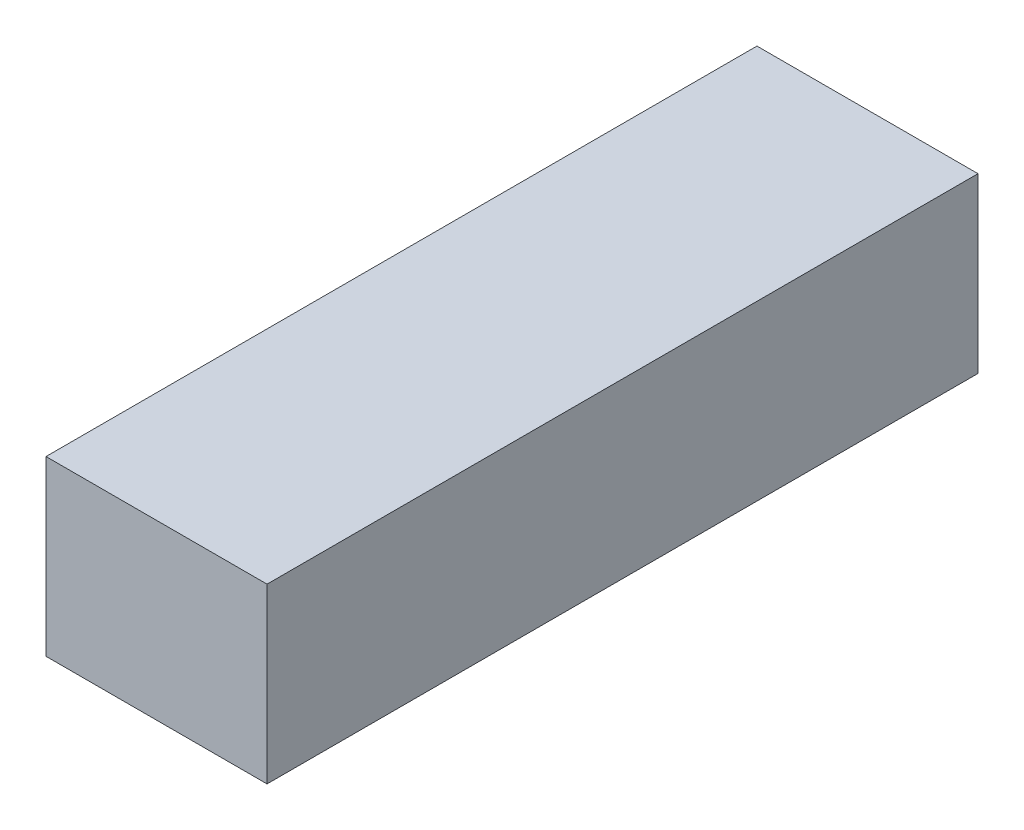
SolidWorks part; units mm, degrees
ref_plane "Front Plane" through (0, 0, 0) normal (0, 0, 1) x (1, 0, 0)
ref_plane "Top Plane" through (0, 0, 0) normal (0, 1, 0) x (1, 0, 0)
ref_plane "Right Plane" through (0, 0, 0) normal (1, 0, 0) x (0, 0, -1)
sketch "Sketch1" plane through (0, 0, 0) normal (0, 1, 0) x (1, 0, 0)
  line L0 (0, 0) -> (0, 139.7) construction
  line L1 (-21.717, 139.7) -> (21.717, 139.7)
  line L2 (-21.717, 139.7) -> (-21.717, 0)
  line L3 (-21.717, 0) -> (21.717, 0)
  line L4 (21.717, 139.7) -> (21.717, 0)
  line L5 (0, -55) -> (0, 55) construction
  line L6 (-55, 0) -> (55, 0) construction
  dimension "D1" = 43.434
  dimension "D2" = 139.7
extrude "Boss-Extrude1" add sketch "Sketch1" along normal blind 34
